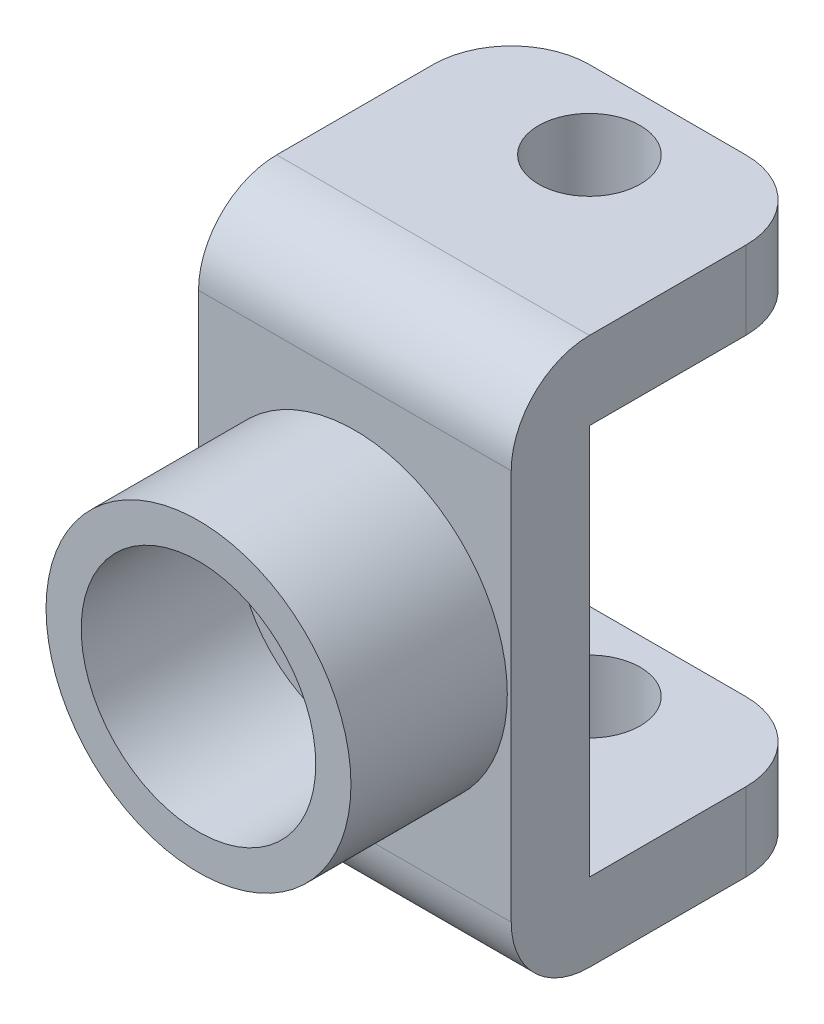
SolidWorks part; units mm, degrees
ref_plane "Front Plane" through (0, 0, 0) normal (0, 0, 1) x (1, 0, 0)
ref_plane "Top Plane" through (0, 0, 0) normal (0, 1, 0) x (1, 0, 0)
ref_plane "Right Plane" through (0, 0, 0) normal (1, 0, 0) x (0, 0, -1)
sketch "Sketch1" plane through (0, 0, 0) normal (0, 0, 1) x (1, 0, 0)
  line L1 (-20, -25) -> (20, -25)
  line L2 (-20, -25) -> (-20, 25)
  line L3 (-20, 25) -> (20, 25)
  line L4 (20, -25) -> (20, 25)
  line L5 (-20, -25) -> (20, 25) construction
  line L6 (-20, 25) -> (20, -25) construction
  point P0 (0, 0)
  dimension "D1" = 40
  dimension "D2" = 50
extrude "Boss-Extrude1" add sketch "Sketch1" along normal blind 10 contours L1 L4 L3 L2
sketch "Sketch3" plane through (0, 0, 0) normal (1, 0, 0) x (0, 0, -1)
  line L0 (-10, -25) -> (-10, 25) construction
  line L1 (-10, -25) -> (30, -25)
  line L2 (-10, -25) -> (-10, -35)
  line L3 (-10, -35) -> (30, -35)
  line L4 (30, -25) -> (30, -35)
  line L5 (-10, -25) -> (0, -25) construction
  line L6 (-10, 25) -> (0, 25) construction
  line L7 (-10, 25) -> (30, 25)
  line L8 (-10, 25) -> (-10, 35)
  line L9 (-10, 35) -> (30, 35)
  line L10 (30, 25) -> (30, 35)
  dimension "D1" = 10
  dimension "D2" = 10
  dimension "D3" = 40
  dimension "D4" = 40
extrude "Boss-Extrude2" add sketch "Sketch3" along normal mid plane 40
fillet "Fillet1" radius 10 6 edges at (0, 35, 10) (0, -35, 10) (-20, -30, -30) (20, -30, -30) (-20, 30, -30) (20, 30, -30)
sketch "Sketch4" plane through (0, 0, 10) normal (0, 0, 1) x (1, 0, 0)
  circle A0 centre (0, 0) radius 19.5
  circle A1 centre (0, 0) radius 15
  dimension "D1" = 30
  dimension "D2" = 39
extrude "Boss-Extrude3" add sketch "Sketch4" along normal blind 20
sketch "Sketch5" plane through (0, -35, 0) normal (0, -1, 0) x (1, 0, 0)
  line L0 (0, -30) -> (0, -20) construction
  line L1 (10, -30) -> (-10, -30) construction
  circle A0 centre (0, -20) radius 6.5
  dimension "D2" = 13
  dimension "D1" = 10
extrude "Cut-Extrude1" cut sketch "Sketch5" against normal blind 100
